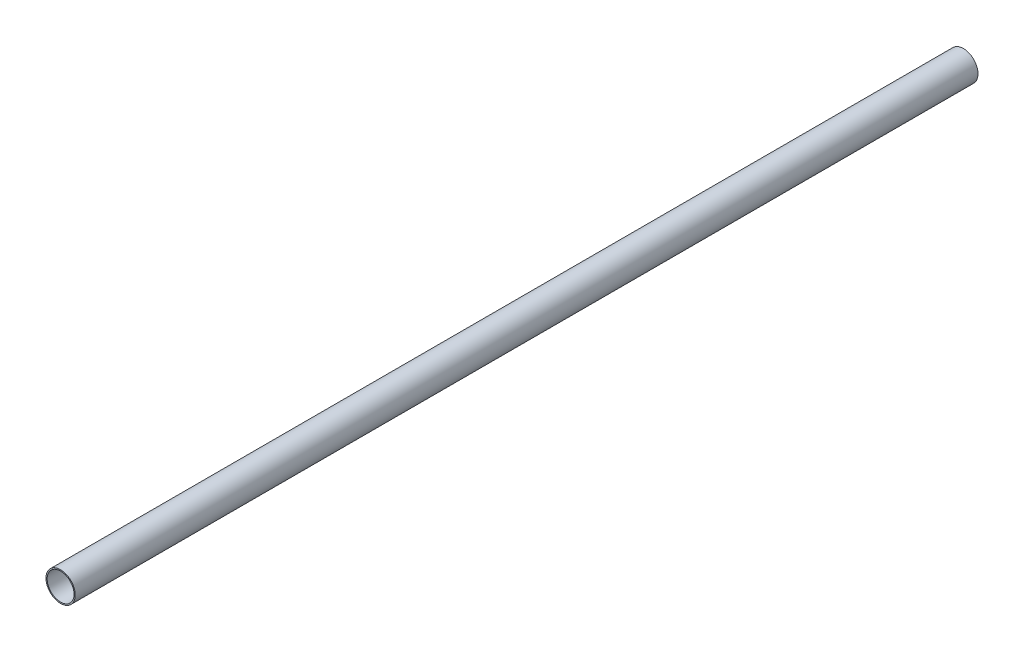
SolidWorks part; units mm, degrees
material "Acrylic (Medium-high impact)"
ref_plane "Front Plane" through (0, 0, 0) normal (0, 0, 1) x (1, 0, 0)
ref_plane "Top Plane" through (0, 0, 0) normal (0, 1, 0) x (1, 0, 0)
ref_plane "Right Plane" through (0, 0, 0) normal (1, 0, 0) x (0, 0, -1)
sketch "Sketch1" plane through (0, 0, 0) normal (0, 0, 1) x (1, 0, 0)
  circle A0 centre (0, 0) radius 10.2235
  circle A1 centre (0, 0) radius 11.1125
  dimension "D1" = 20.447
  dimension "D2" = 22.225
extrude "Boss-Extrude1" add sketch "Sketch1" along normal blind 685.8
